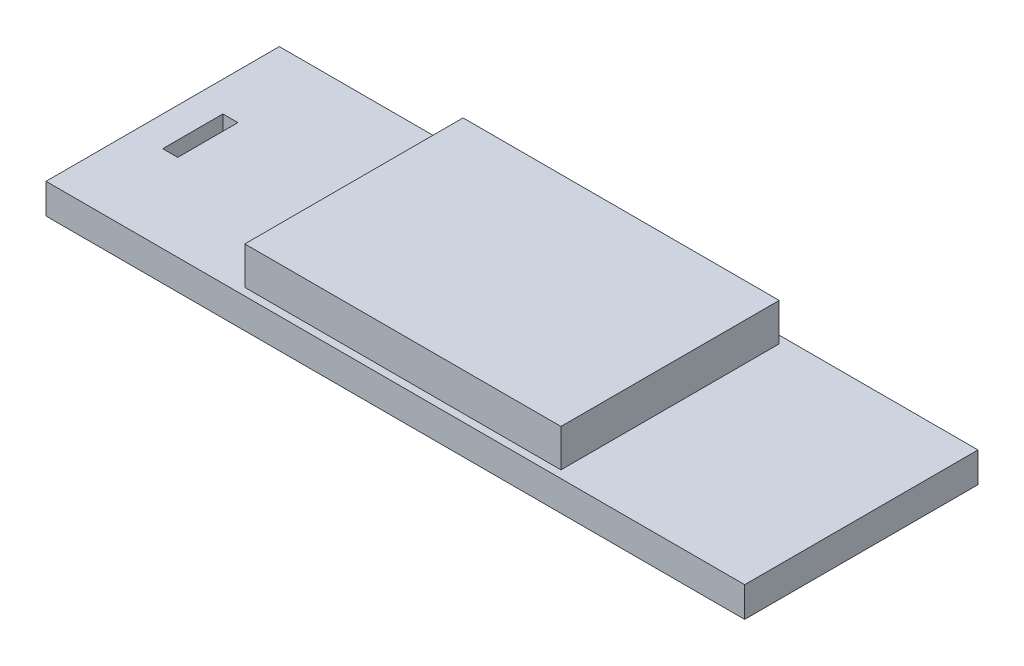
SolidWorks part; units mm, degrees
ref_plane "Front Plane" through (0, 0, 0) normal (0, 0, 1) x (1, 0, 0)
ref_plane "Top Plane" through (0, 0, 0) normal (0, 1, 0) x (1, 0, 0)
ref_plane "Right Plane" through (0, 0, 0) normal (1, 0, 0) x (0, 0, -1)
sketch "Sk_Base" plane through (0, 0, 0) normal (0, 1, 0) x (1, 0, 0)
  line L1 (0, -15.5) -> (92.82, -15.5)
  line L2 (0, -15.5) -> (0, 15.5)
  line L3 (0, 15.5) -> (92.82, 15.5)
  line L4 (92.82, -15.5) -> (92.82, 15.5)
extrude "Base Plate" add sketch "Sk_Base" along normal blind 4
ref_plane "Plane_BaseTop" through (0, 4, 0) normal (0, 1, 0) x (1, 0, 0)
sketch "Sk_Block" plane through (0, 4, 0) normal (0, 1, 0) x (1, 0, 0)
  line L1 (25.41, -14.5) -> (67.41, -14.5)
  line L2 (25.41, -14.5) -> (25.41, 14.5)
  line L3 (25.41, 14.5) -> (67.41, 14.5)
  line L4 (67.41, -14.5) -> (67.41, 14.5)
extrude "Camera Block" add sketch "Sk_Block" along normal blind 5
sketch "Sk_PinHole" plane through (0, 0, 0) normal (0, 1, 0) x (1, 0, 0)
  circle A0 centre (46.41, 0) radius 1.8
extrude "Slide Pin Hole" cut sketch "Sk_PinHole" along normal blind 4
sketch "Sk_TieSlots" plane through (0, 0, 0) normal (0, 1, 0) x (1, 0, 0)
  line L1 (4, -4) -> (6, -4)
  line L2 (4, -4) -> (4, 4)
  line L3 (4, 4) -> (6, 4)
  line L4 (6, -4) -> (6, 4)
  line L6 (22, -4) -> (24, -4)
  line L7 (22, -4) -> (22, 4)
  line L8 (22, 4) -> (24, 4)
  line L9 (24, -4) -> (24, 4)
extrude "Cable Tie Slots" cut sketch "Sk_TieSlots" against normal through all and the other way through all
